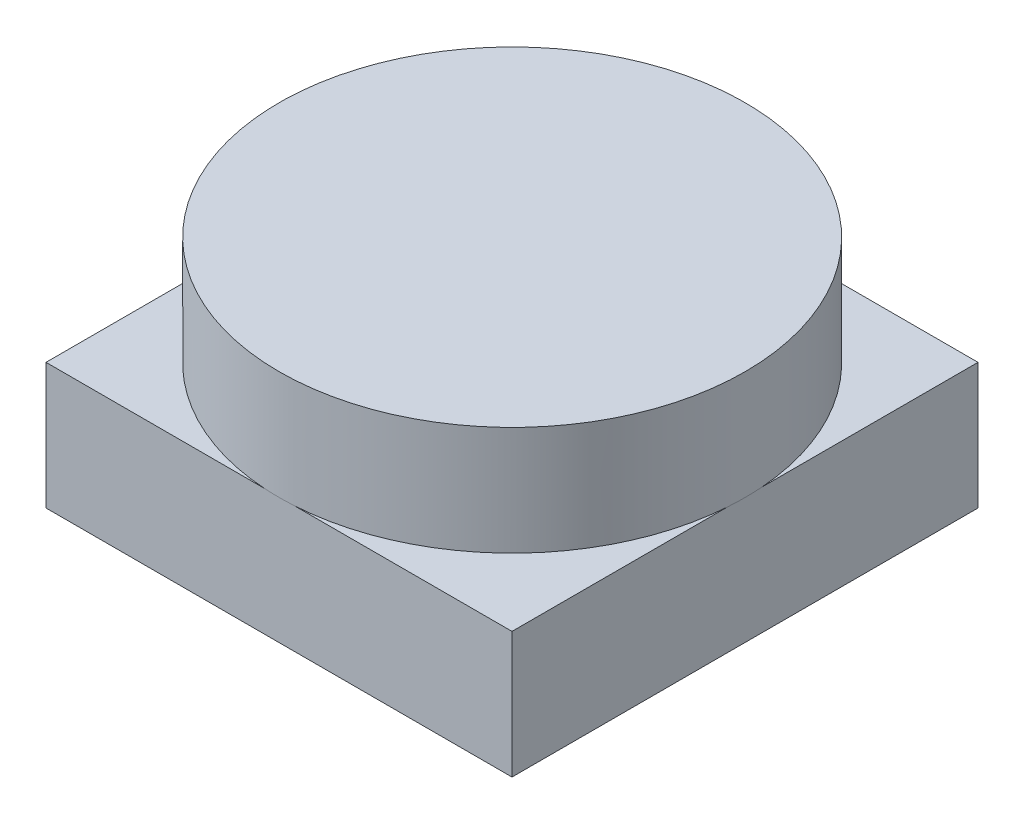
SolidWorks part; units mm, degrees
ref_plane "Front Plane" through (0, 0, 0) normal (0, 0, 1) x (1, 0, 0)
ref_plane "Top Plane" through (0, 0, 0) normal (0, 1, 0) x (1, 0, 0)
ref_plane "Right Plane" through (0, 0, 0) normal (1, 0, 0) x (0, 0, -1)
sketch "Sketch1" plane through (0, 0, 0) normal (0, 1, 0) x (1, 0, 0)
  line L1 (-34.1025, 37.6552) -> (42.8975, 37.6552)
  line L2 (-34.1025, 37.6552) -> (-34.1025, -39.3448)
  line L3 (-34.1025, -39.3448) -> (42.8975, -39.3448)
  line L4 (42.8975, 37.6552) -> (42.8975, -39.3448)
  dimension "D1" = 77
  dimension "D2" = 77
extrude "Boss-Extrude1" add sketch "Sketch1" along normal blind 20.85
sketch "Sketch3" plane through (0, 20.85, 0) normal (0, 1, 0) x (1, 0, 0)
  circle A0 centre (4.5, -0.9228) radius 38.5
  point P2 (0, 0)
  dimension "D1" = 77
extrude "Boss-Extrude2" add sketch "Sketch3" along normal blind 18 contours A0
